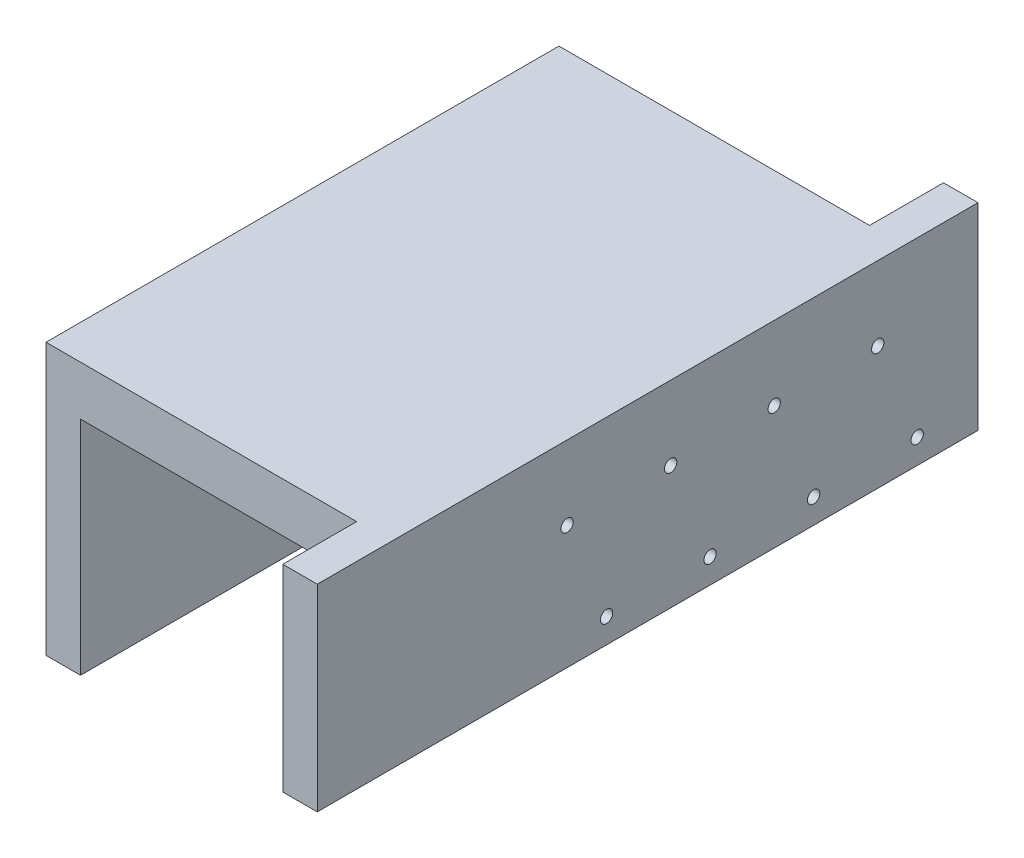
SolidWorks part; units mm, degrees
ref_plane "Front Plane" through (0, 0, 0) normal (0, 0, 1) x (1, 0, 0)
ref_plane "Top Plane" through (0, 0, 0) normal (0, 1, 0) x (1, 0, 0)
ref_plane "Right Plane" through (0, 0, 0) normal (1, 0, 0) x (0, 0, -1)
sketch "Sketch1" plane through (0, 0, 0) normal (0, 0, 1) x (1, 0, 0)
  line L1 (0, 0) -> (70, 0)
  line L2 (0, 0) -> (0, 55)
  line L3 (0, 55) -> (70, 55)
  line L4 (70, 0) -> (70, 55)
  dimension "D1" = 70
  dimension "D2" = 55
extrude "Boss-Extrude1" add sketch "Sketch1" along normal blind 134
sketch "Sketch2" plane through (0, 0, 134) normal (0, 0, 1) x (1, 0, 0)
  line L0 (7, 0) -> (7, 45)
  line L1 (0, 0) -> (70, 0) construction
  line L2 (7, 45) -> (63, 45)
  line L3 (63, 45) -> (63, 15)
  line L4 (60, 0) -> (7, 0)
  line L5 (0, 55) -> (0, 0) construction
  line L6 (70, 0) -> (70, 55) construction
  line L7 (70, 55) -> (0, 55) construction
  line L8 (63, 15) -> (70, 15)
  line L9 (70, 15) -> (70, 0)
  line L10 (70, 0) -> (60, 0)
  dimension "D1" = 7
  dimension "D2" = 7
  dimension "D3" = 10
  dimension "D4" = 15
extrude "Cut-Extrude1" cut sketch "Sketch2" against normal through all both and the other way through all
sketch "Sketch4" plane through (70, 0, 0) normal (1, 0, 0) x (0, 0, -1)
  line L0 (0, 15) -> (-134, 15) construction
  circle A0 centre (-83.3318, 40) radius 1.25
  circle A1 centre (-75.3318, 20) radius 1.25
  circle A2 centre (-62.3318, 40) radius 1.25
  circle A3 centre (-54.3318, 20) radius 1.25
  circle A4 centre (-41.3318, 40) radius 1.25
  circle A5 centre (-33.3318, 20) radius 1.25
  circle A6 centre (-20.3318, 40) radius 1.25
  circle A7 centre (-12.3318, 20) radius 1.25
  dimension "D1" = 2.5
  dimension "D2" = 2.5
  dimension "D5" = 2.5
  dimension "D6" = 2.5
  dimension "D10" = 2.5
  dimension "D11" = 2.5
  dimension "D14" = 2.5
  dimension "D15" = 2.5
  dimension "D3" = 8
  dimension "D4" = 20
  dimension "D7" = 8
  dimension "D8" = 20
  dimension "D9" = 13
  dimension "D12" = 8
  dimension "D13" = 20
  dimension "D16" = 8
  dimension "D17" = 20
  dimension "D18" = 13
  dimension "D19" = 13
  dimension "D20" = 5
  dimension "D21" = 5
  dimension "D22" = 5
  dimension "D23" = 5
extrude "Cut-Extrude4" cut sketch "Sketch4" against normal up to surface (7 mm away) up to face at (63, 30, 67)
sketch "Sketch5" plane through (0, 0, 0) normal (-1, 0, 0) x (0, 0, 1)
  line L0 (0, 27.5) -> (134, 27.5) construction
  line L1 (0, 55) -> (0, 0) construction
  line L2 (134, 55) -> (134, 0) construction
  line L3 (134, 0) -> (0, 0) construction
  line L4 (14.9857, 55) -> (119.0143, 55)
  line L5 (14.9857, 55) -> (14.9857, 0)
  line L6 (14.9857, 0) -> (119.0143, 0)
  line L7 (119.0143, 55) -> (119.0143, 0)
  line L8 (14.9857, 55) -> (119.0143, 0) construction
  line L9 (14.9857, 0) -> (119.0143, 55) construction
  line L11 (0, 55) -> (14.9857, 55)
  line L12 (0, 55) -> (0, 0)
  line L13 (0, 0) -> (14.9857, 0)
  line L14 (14.9857, 55) -> (14.9857, 0)
  line L15 (119.0143, 55) -> (134, 55)
  line L16 (119.0143, 55) -> (119.0143, 0)
  line L17 (119.0143, 0) -> (134, 0)
  line L18 (134, 55) -> (134, 0)
  point P6 (67, 27.5)
  line M2 (0, 55) -> (0, 0)
  line M3 (0, 0) -> (134, 0)
  line M4 (134, 0) -> (134, 55)
  line M5 (134, 55) -> (0, 55)
extrude "Cut-Extrude5" cut sketch "Sketch5" against normal blind 63 contours L5 M5 M2 M3 | L7 M5 M3 M4
sketch "Sketch8" plane through (7, 0, 0) normal (1, 0, 0) x (0, 0, 1)
  line L0 (66.6613, -11.0845) -> (66.6613, -49.1845) construction
  line L3 (45.7063, -26.7544) -> (87.6163, -26.7544) construction
  line L6 (52.6913, -14.0544) -> (52.6913, -39.4544) construction
  line L7 (59.6763, -11.0845) -> (59.6763, -49.1845) construction
  line L8 (73.6463, -11.0845) -> (73.6463, -49.1845) construction
  line L15 (87.6163, -11.0845) -> (45.7063, -11.0845) construction
  line L16 (45.7063, -11.0845) -> (45.7063, -49.1845) construction
  line L17 (45.7063, -49.1845) -> (87.6163, -49.1845) construction
  line L18 (87.6163, -49.1845) -> (87.6163, -11.0845) construction
  circle A0 centre (52.6913, -14.0544) radius 1
  circle A1 centre (80.6313, -14.0544) radius 1
  circle A2 centre (52.6913, -39.4544) radius 1
  circle A3 centre (80.6313, -39.4544) radius 1
  circle A4 centre (66.6613, -30.1345) radius 1
  point P0 (52.6913, -14.0544)
  point P2 (80.6313, -14.0544)
  point P4 (52.6913, -39.4544)
  point P6 (80.6313, -39.4544)
  point P32 (52.6913, -14.0544)
  point P39 (52.6913, -39.4544)
  point P42 (54.7162, -14.1752)
  dimension "D3" = 2
  dimension "D4" = 2
  dimension "D1" = 27.94
  dimension "D2" = 25.4
hole_wizard "CSK for M3 Countersunk Flat Head Screw1" positions "Sketch8" profile "Sketch9" countersink size "M3" standard "ISO"
sketch "Sketch9" plane through (7, 39.4544, 52.6913) normal (0, 1, 0) x (0, 0, -1)
  line L0 (0, 0) -> (0, 11.0215)
  line L1 (0, 11.0215) -> (1.7, 10)
  line L2 (1.7, 10) -> (1.7, 1.45)
  line L3 (1.7, 1.45) -> (3.15, 0)
  line L5 (3.15, 0) -> (0, 0)
  line L6 (-1.7, 1.45) -> (-3.15, 0) construction
  line L10 (0, 11.0215) -> (-1.7, 10) construction
  line L11 (0, -6.35) -> (0, 107.95) construction
  dimension "Hole Dia." = 3.4
  dimension "Hole Depth" = 10
  dimension "Near C'Sink Dia." = 6.3
  dimension "Near C'Sink Angle" = 90
  dimension "Drill Angle" = 118
